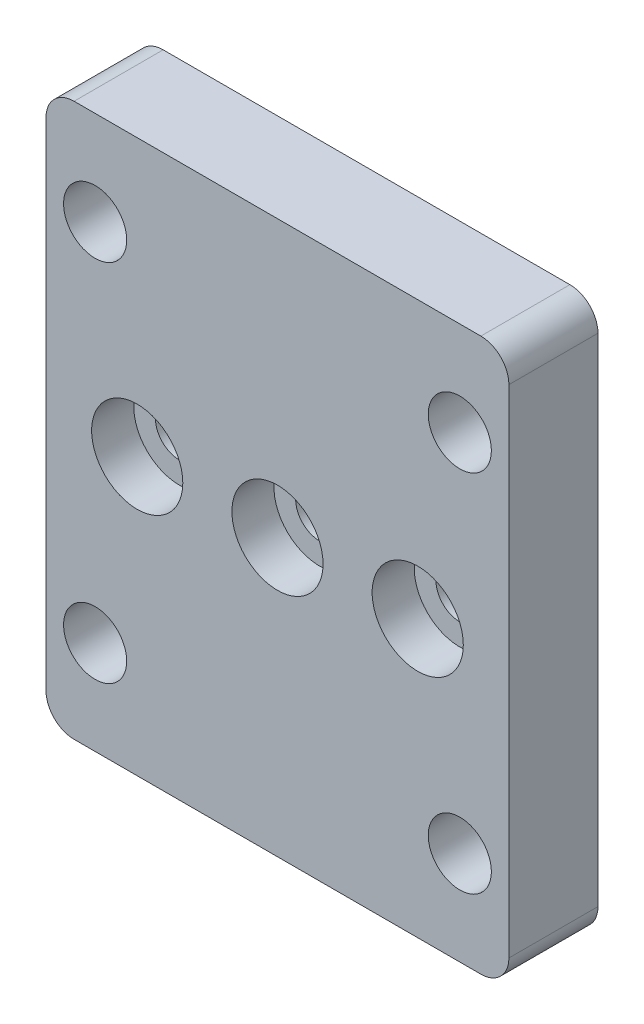
SolidWorks part; units mm, degrees
material "AISI 1045 Steel, cold drawn"
ref_plane "Front Plane" through (0, 0, 0) normal (0, 0, 1) x (1, 0, 0)
ref_plane "Top Plane" through (0, 0, 0) normal (0, 1, 0) x (1, 0, 0)
ref_plane "Right Plane" through (0, 0, 0) normal (1, 0, 0) x (0, 0, -1)
sketch "Sketch1" plane through (0, 0, 0) normal (0, 0, 1) x (1, 0, 0)
  line L0 (10, 0) -> (-10, 0) construction
  line L1 (13, -13) -> (-13, -13) construction
  line L2 (13, -13) -> (13, 13) construction
  line L3 (13, 13) -> (-13, 13) construction
  line L4 (-13, -13) -> (-13, 13) construction
  line L5 (13, -13) -> (-13, 13) construction
  line L6 (13, 13) -> (-13, -13) construction
  line L7 (16.5, -19.7) -> (-16.5, -19.7)
  line L8 (16.5, -19.7) -> (16.5, 19.7)
  line L9 (16.5, 19.7) -> (-16.5, 19.7)
  line L10 (-16.5, -19.7) -> (-16.5, 19.7)
  line L11 (16.5, -19.7) -> (-16.5, 19.7) construction
  line L12 (16.5, 19.7) -> (-16.5, -19.7) construction
  point P0 (0, 0)
  point P6 (0, 0)
  point P14 (0, 0)
  dimension "D1" = 26
  dimension "D2" = 20
  dimension "D3" = 33
  dimension "D4" = 39.4
extrude "Boss-Extrude1" add sketch "Sketch1" along normal blind 6.35
hole_wizard "CBORE for M3 SHCS1" positions "Sketch2" profile "Sketch3" counterbore size "M3" standard "ANSI Metric" end condition through all
sketch "Sketch2" plane through (0, 0, 6.35) normal (0, 0, 1) x (1, 0, 0)
  line L0 (13, 13) -> (-13, -13) construction
  point P0 (-10, 0)
  point P3 (0, 0)
  point P7 (10, 0)
sketch "Sketch3" plane through (-10, 0, 6.35) normal (1, 0, 0) x (0, -1, 0)
  line L0 (0, 0) -> (0, 6.35)
  line L1 (0, 6.35) -> (1.7, 6.35)
  line L3 (1.7, 6.35) -> (1.7, 3)
  line L4 (1.7, 3) -> (3.25, 3)
  line L5 (3.25, 3) -> (3.25, 0)
  line L7 (3.25, 0) -> (0, 0)
  line L11 (0, -6.35) -> (0, 107.95) construction
  dimension "Thru Hole Dia." = 3.4
  dimension "Thru Hole Depth" = 6.35
  dimension "C'Bore Dia." = 6.5
  dimension "C'Bore Depth" = 3
hole_wizard "M4 Clearance Hole1" positions "Sketch4" profile "Sketch5" hole size "M4" standard "ANSI Metric" end condition through all
sketch "Sketch4" plane through (0, 0, 6.35) normal (0, 0, 1) x (1, 0, 0)
  point P0 (-13, 13)
  point P3 (-13, -13)
  point P6 (13, -13)
  point P9 (13, 13)
sketch "Sketch5" plane through (-13, 13, 6.35) normal (1, 0, 0) x (0, -1, 0)
  line L0 (0, 0) -> (0, 6.35)
  line L1 (0, 6.35) -> (2.25, 6.35)
  line L2 (2.25, 6.35) -> (2.25, 0)
  line L5 (2.25, 0) -> (0, 0)
  line L11 (0, -6.35) -> (0, 107.95) construction
  dimension "Thru Hole Dia." = 4.5
  dimension "Thru Hole Depth" = 6.35
fillet "Fillet1" radius 2 4 edges at (16.5, 19.7, 3.175) (16.5, -19.7, 3.175) (-16.5, -19.7, 3.175) (-16.5, 19.7, 3.175)
